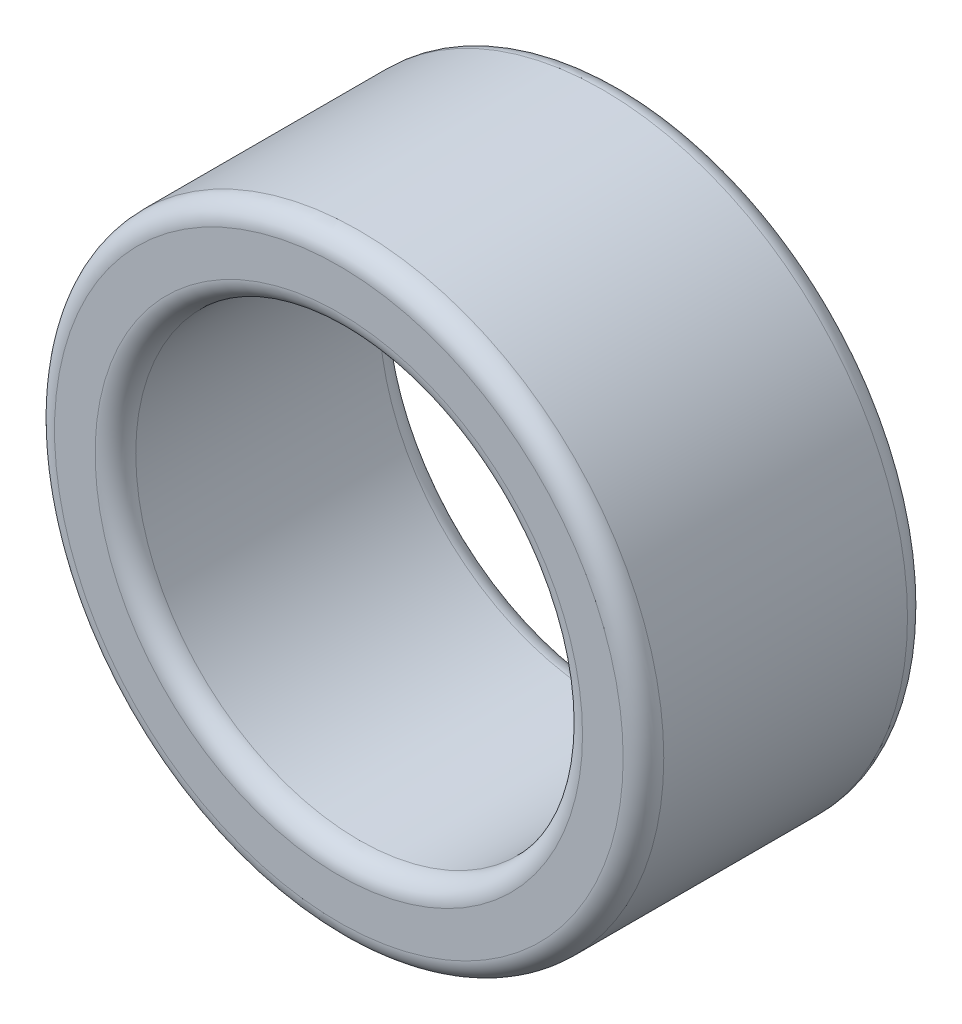
SolidWorks part; units mm, degrees
material "Silicon Rubber"
ref_plane "Front Plane" through (0, 0, 0) normal (0, 0, 1) x (1, 0, 0)
ref_plane "Top Plane" through (0, 0, 0) normal (0, 1, 0) x (1, 0, 0)
ref_plane "Right Plane" through (0, 0, 0) normal (1, 0, 0) x (0, 0, -1)
sketch "Sketch2" plane through (0, 0, 0) normal (0, 0, 1) x (1, 0, 0)
  circle A0 centre (0, 0) radius 381
  dimension "D1" = 762
extrude "Boss-Extrude1" add sketch "Sketch2" along normal blind 355.6
sketch "Sketch3" plane through (0, 0, 355.6) normal (0, 0, 1) x (1, 0, 0)
  circle A0 centre (0, 0) radius 279.4
  dimension "D1" = 558.8
extrude "Cut-Extrude1" cut sketch "Sketch3" against normal through all
fillet "Fillet3" radius 25.4 2 edges at (381, 0, 0) (381, 0, 355.6)
fillet "Fillet4" radius 25.4 2 edges at (279.4, 0, 0) (279.4, 0, 355.6)
scale "Scale1" scale about centroid uniform scaling yes scale factor 0.15
